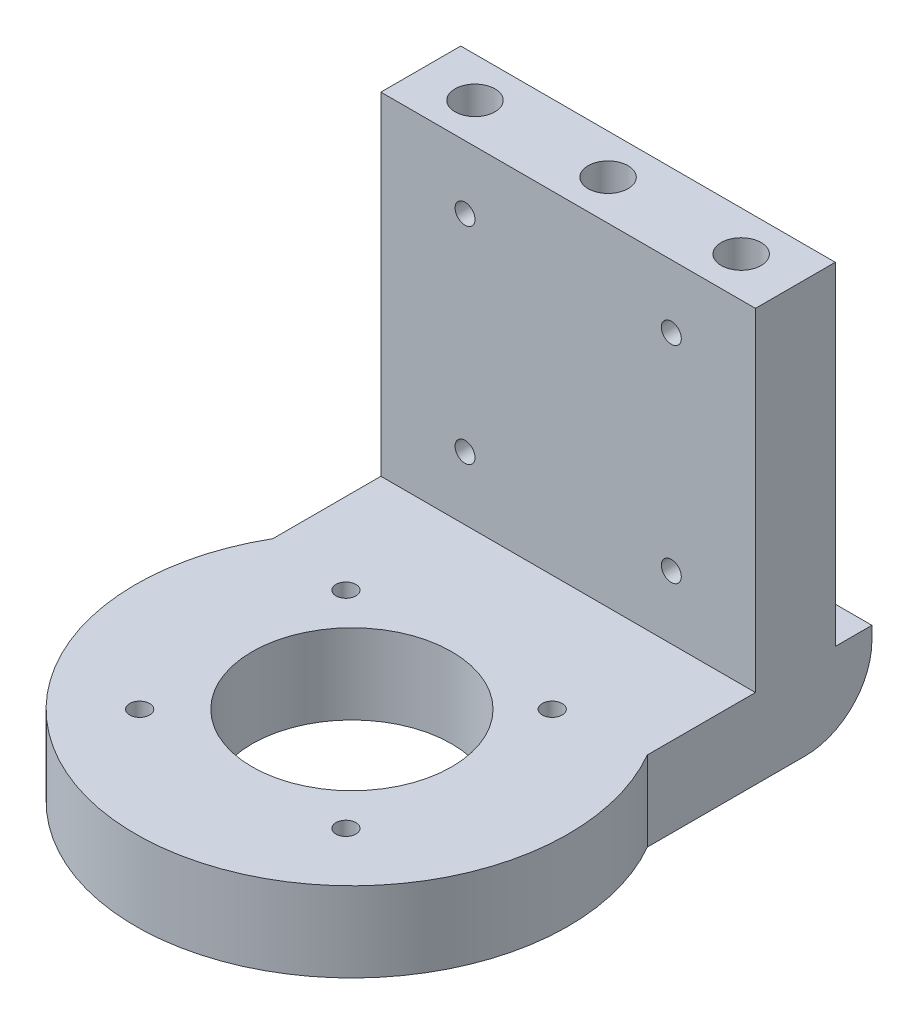
SolidWorks part; units mm, degrees
material "5052-H32"
ref_plane "前视基准面" through (0, 0, 0) normal (0, 0, 1) x (1, 0, 0)
ref_plane "上视基准面" through (0, 0, 0) normal (0, 1, 0) x (1, 0, 0)
ref_plane "右视基准面" through (0, 0, 0) normal (1, 0, 0) x (0, 0, -1)
sketch "草图1" plane through (0, 0, 0) normal (0, 1, 0) x (1, 0, 0)
  circle A0 centre (0, 0) radius 32.5
  circle A1 centre (0, 0) radius 15
extrude "凸台-拉伸1" add sketch "草图1" along normal blind 12
sketch "草图2" plane through (0, 12, 0) normal (0, 1, 0) x (1, 0, 0)
  circle A0 centre (-15.95, 15.05) radius 1.5
  circle A1 centre (15.05, 15.05) radius 1.5
  circle A2 centre (15.05, -15.95) radius 1.5
  circle A3 centre (-15.95, -15.95) radius 1.5
extrude "切除-拉伸1" cut sketch "草图2" against normal blind 12
sketch "草图3" plane through (0, 12, 0) normal (0, 1, 0) x (1, 0, 0)
  line L0 (0, 0) -> (28.1458, 16.25)
  line L1 (0, 0) -> (-28.1458, 16.25)
  line L2 (0, 0) -> (0, 50)
  line L3 (0, 50) -> (-28.1458, 50)
  line L4 (-28.1458, 50) -> (-28.1458, 16.25)
  line L5 (0, 50) -> (28.1458, 50)
  line L6 (28.1458, 50) -> (28.1458, 16.25)
  circle A0 centre (0, 0) radius 32.5 construction
  circle M10 centre (0, 0) radius 32.5
extrude "凸台-拉伸2" add sketch "草图3" against normal blind 12 contours L3 L4 L2 M10 | L6 L5 L2 M10
sketch "草图4" plane through (0, 12, 0) normal (0, 1, 0) x (1, 0, 0)
  line L0 (28.1458, 32.5) -> (28.1458, 44.5)
  line L1 (0, 32.5) -> (28.1458, 32.5)
  line L2 (28.1458, 50) -> (28.1458, 16.25) construction
  line L3 (28.1458, 44.5) -> (-28.1458, 44.5)
  line L4 (-28.1458, 50) -> (-28.1458, 16.25) construction
  line L5 (-28.1458, 44.5) -> (-28.1458, 32.5)
  line L6 (-28.1458, 32.5) -> (0, 32.5)
  circle A0 centre (0, 0) radius 32.5
extrude "凸台-拉伸3" add sketch "草图4" along normal blind 50 contours L6 L1 L0 L3 L5
sketch "草图5" plane through (0, 62, 0) normal (0, 1, 0) x (1, 0, 0)
  circle A0 centre (0, 38.5) radius 3
  circle A1 centre (20, 38.5) radius 3
  circle A2 centre (-20, 38.5) radius 3
extrude "切除-拉伸2" cut sketch "草图5" against normal blind 5
sketch "草图6" plane through (0, 0, 0) normal (0, -1, 0) x (1, 0, 0)
  circle A1 centre (15.05, 15.95) radius 3
  circle A2 centre (-15.95, 15.95) radius 3
  circle A3 centre (-15.95, -15.05) radius 3
  circle A4 centre (15.05, -15.05) radius 3
extrude "切除-拉伸3" cut sketch "草图6" against normal blind 3
sketch "草图7" plane through (0, 0, -44.5) normal (0, 0, -1) x (-1, 0, 0)
  line L0 (-28.1458, 12) -> (-28.1458, 37)
  line L1 (-28.1458, 62) -> (-28.1458, 12) construction
  circle A0 centre (15.5, 52.5) radius 1.5
  circle A1 centre (15.5, 21.5) radius 1.5
  circle A2 centre (-15.5, 52.5) radius 1.5
  circle A3 centre (-15.5, 21.5) radius 1.5
  point P6 (0, 0)
  point P7 (0, 0)
extrude "切除-拉伸9" cut sketch "草图7" against normal through all contours A2 | A3 | A1 | A0
fillet "圆角1" radius 10 1 edges at (0, 0, -50)
